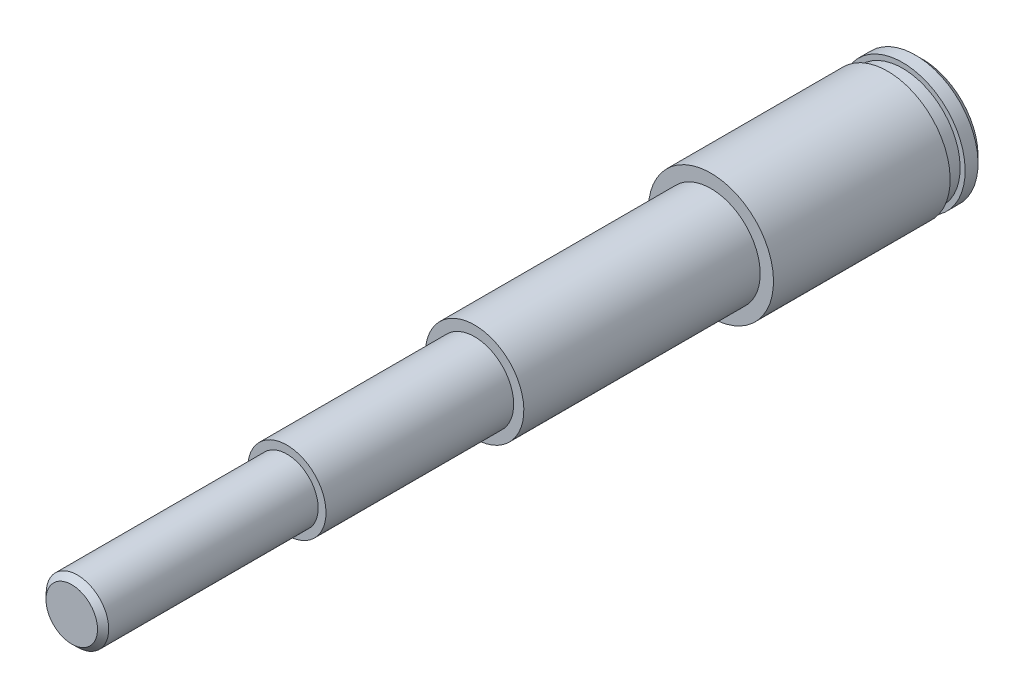
SolidWorks part; units mm, degrees
ref_plane "Front Plane" through (0, 0, 0) normal (0, 0, 1) x (1, 0, 0)
ref_plane "Top Plane" through (0, 0, 0) normal (0, 1, 0) x (1, 0, 0)
ref_plane "Right Plane" through (0, 0, 0) normal (1, 0, 0) x (0, 0, -1)
sketch "Sketch1" plane through (0, 0, 0) normal (1, 0, 0) x (0, 0, -1)
  line L0 (8.1197, 0.3638) -> (-4, 0.3638) construction
  line L1 (-19.8068, 0.3638) -> (-19.8068, 1.6718)
  line L3 (-19.5171, 1.9513) -> (-8.8833, 1.9513)
  line L4 (0, 0.3638) -> (0, 2.2587) construction
  line L5 (-19.8068, 0.3638) -> (23.3793, 0.3638)
  line L7 (0.6455, 2.3482) -> (0.6455, 2.8638)
  line L8 (0.6455, 2.8638) -> (12.6456, 2.8638)
  line L9 (12.6456, 2.8638) -> (12.6456, 3.5388)
  line L10 (12.6456, 3.5388) -> (21.615, 3.5388)
  line L11 (23.0303, 3.5388) -> (23.3793, 3.1898)
  line L12 (23.3793, 3.1898) -> (23.3793, 0.3638)
  line L13 (-8.8833, 1.9513) -> (-8.8833, 2.3482)
  line L14 (-8.8833, 2.3482) -> (0.6455, 2.3482)
  line L15 (-19.5171, 1.9513) -> (-19.8068, 1.6718)
  line L20 (22.377, 3.5388) -> (23.0303, 3.5388)
  line L21 (21.615, 3.5388) -> (21.615, 3.2848)
  line L22 (22.377, 3.5388) -> (22.377, 3.2848)
  line L23 (21.615, 3.2848) -> (22.377, 3.2848)
  dimension "D1" = 3.175
  dimension "D2" = 3.9687
  dimension "D3" = 0.254
  dimension "D4" = 0.762
  dimension "D5" = 5
  dimension "D6" = 6.35
revolve "Revolve1" add sketch "Sketch1" angle 360 about L5
